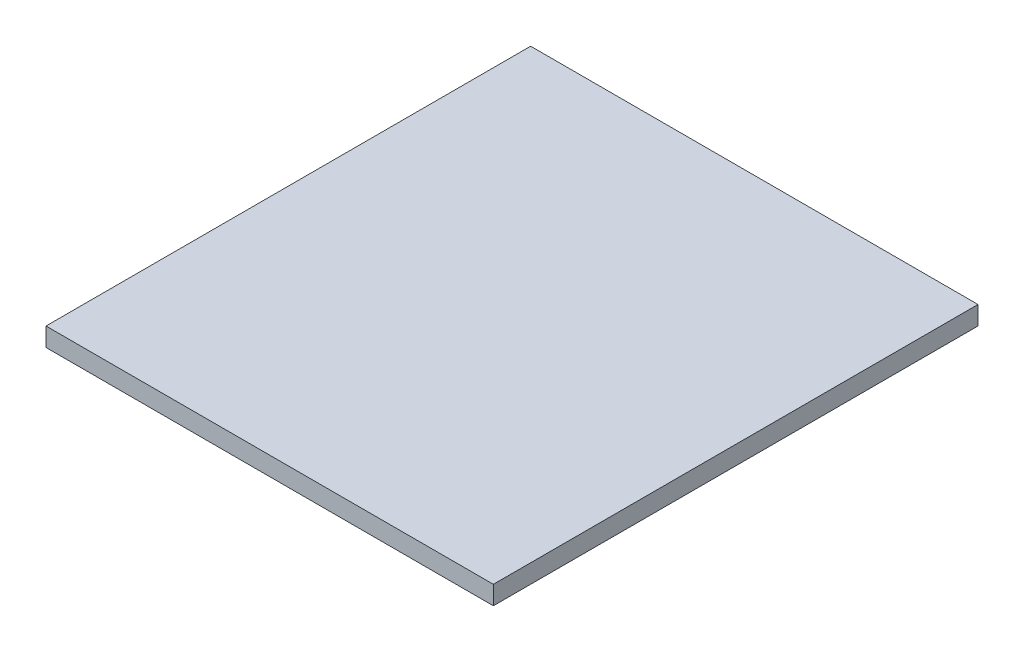
SolidWorks part; units mm, degrees
material "Acrylic (Medium-high impact)"
ref_plane "Front Plane" through (0, 0, 0) normal (0, 0, 1) x (1, 0, 0)
ref_plane "Top Plane" through (0, 0, 0) normal (0, 1, 0) x (1, 0, 0)
ref_plane "Right Plane" through (0, 0, 0) normal (1, 0, 0) x (0, 0, -1)
sketch "Sketch1" plane through (0, 0, 0) normal (0, 1, 0) x (1, 0, 0)
  line L1 (-114.3, 123.825) -> (114.3, 123.825)
  line L2 (-114.3, 123.825) -> (-114.3, -123.825)
  line L3 (-114.3, -123.825) -> (114.3, -123.825)
  line L4 (114.3, 123.825) -> (114.3, -123.825)
  line L5 (-114.3, 123.825) -> (114.3, -123.825) construction
  line L6 (-114.3, -123.825) -> (114.3, 123.825) construction
  point P0 (0, 0)
  dimension "D1" = 228.6
  dimension "D2" = 247.65
extrude "Boss-Extrude1" add sketch "Sketch1" along normal blind 9.525
